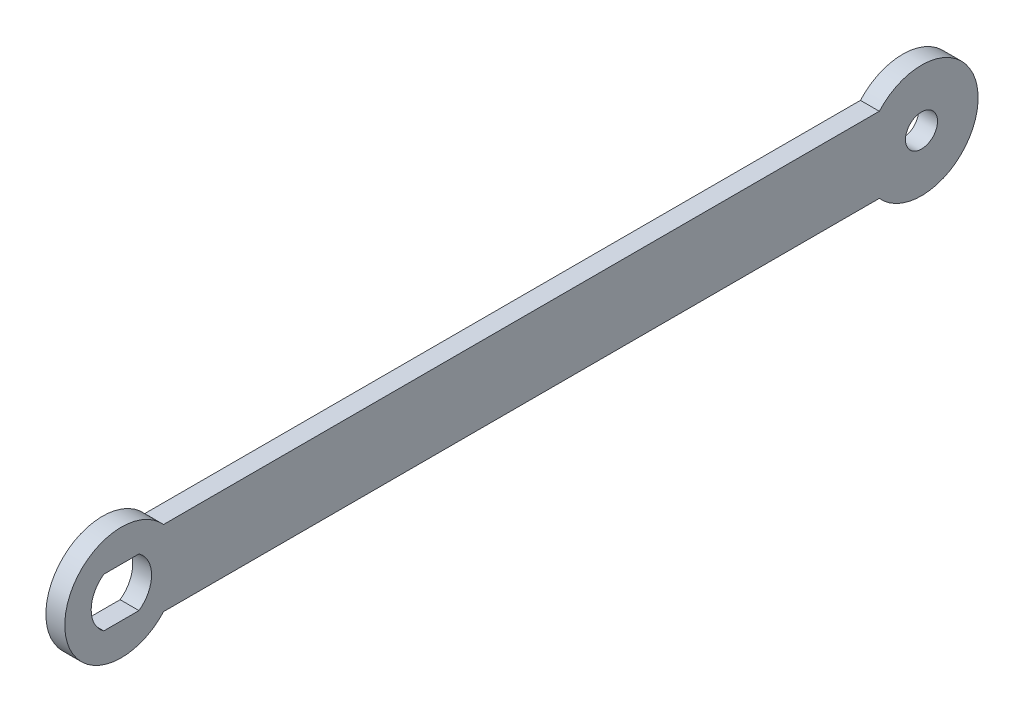
SolidWorks part; units mm, degrees
ref_plane "Face" through (0, 0, 0) normal (0, 0, 1) x (1, 0, 0)
ref_plane "Dessus" through (0, 0, 0) normal (0, 1, 0) x (1, 0, 0)
ref_plane "Droite" through (0, 0, 0) normal (1, 0, 0) x (0, 0, -1)
sketch "Esquisse1" plane through (0, 0, 0) normal (1, 0, 0) x (0, 0, -1)
  line L0 (-4.6637, -6.5) -> (4.6637, -6.5)
  line L1 (11.1803, 10) -> (200.8197, 10)
  line L3 (11.1803, -10) -> (200.8197, -10)
  line L5 (-4.6637, 6.5) -> (4.6637, 6.5)
  arc A0 (-4.6637, 6.5) -> (-4.6637, -6.5) centre (0, 0) ccw
  arc A1 (11.1803, 10) -> (11.1803, -10) centre (0, 0) ccw
  arc A3 (200.8197, -10) -> (200.8197, 10) centre (212, 0) ccw
  arc A5 (4.6637, -6.5) -> (4.6637, 6.5) centre (0, 0) ccw
  dimension "D1" = 10
  dimension "D6" = 16
  dimension "D2" = 20
  dimension "D7" = 6.5
  dimension "D8" = 6.5
extrude "Boss.-Extru.1" add sketch "Esquisse1" along normal blind 5
hole_wizard "Trou taraudé M101" positions "Esquisse5" profile "Esquisse4" tap size "M10" standard "Iso" end condition up to next
sketch "Esquisse5" plane through (5, 0, 0) normal (1, 0, 0) x (0, 0, -1)
  point P9 (212, 0)
sketch "Esquisse4" plane through (5, 0, -212) normal (0, 1, 0) x (0, 0, -1)
  line L0 (0, 0) -> (0, 5)
  line L1 (0, 5) -> (4.25, 5)
  line L2 (4.25, 5) -> (4.25, 0)
  line L5 (4.25, 0) -> (0, 0)
  line L11 (0, -6.35) -> (0, 107.95) construction
  dimension "Diamètre du trou pour taraudage jusqu'au prochain" = 8.5
  dimension "Profondeur du trou pour taraudage jusqu'au prochain" = 5
cosmetic thread "Filetage de perçage1" parameters "D2"=10
